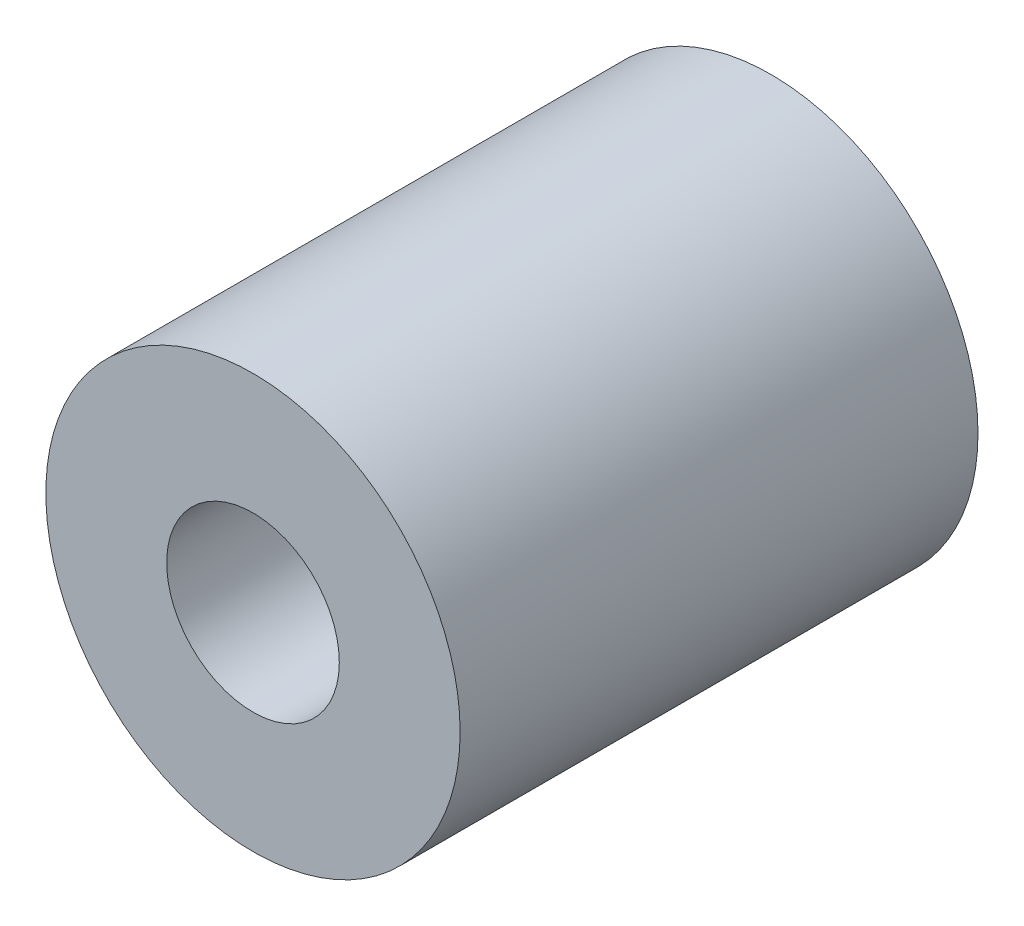
SolidWorks part; units mm, degrees
material "AISI 316 Stainless Steel Sheet (SS)"
ref_plane "Front Plane" through (0, 0, 0) normal (0, 0, 1) x (1, 0, 0)
ref_plane "Top Plane" through (0, 0, 0) normal (0, 1, 0) x (1, 0, 0)
ref_plane "Right Plane" through (0, 0, 0) normal (1, 0, 0) x (0, 0, -1)
sketch "Sketch1" plane through (0, 0, 0) normal (0, 0, 1) x (1, 0, 0)
  circle A0 centre (0, 0) radius 12
  circle A1 centre (0, 0) radius 5
  dimension "D1" = 24
  dimension "D2" = 10
extrude "Boss-Extrude1" add sketch "Sketch1" along normal blind 30
